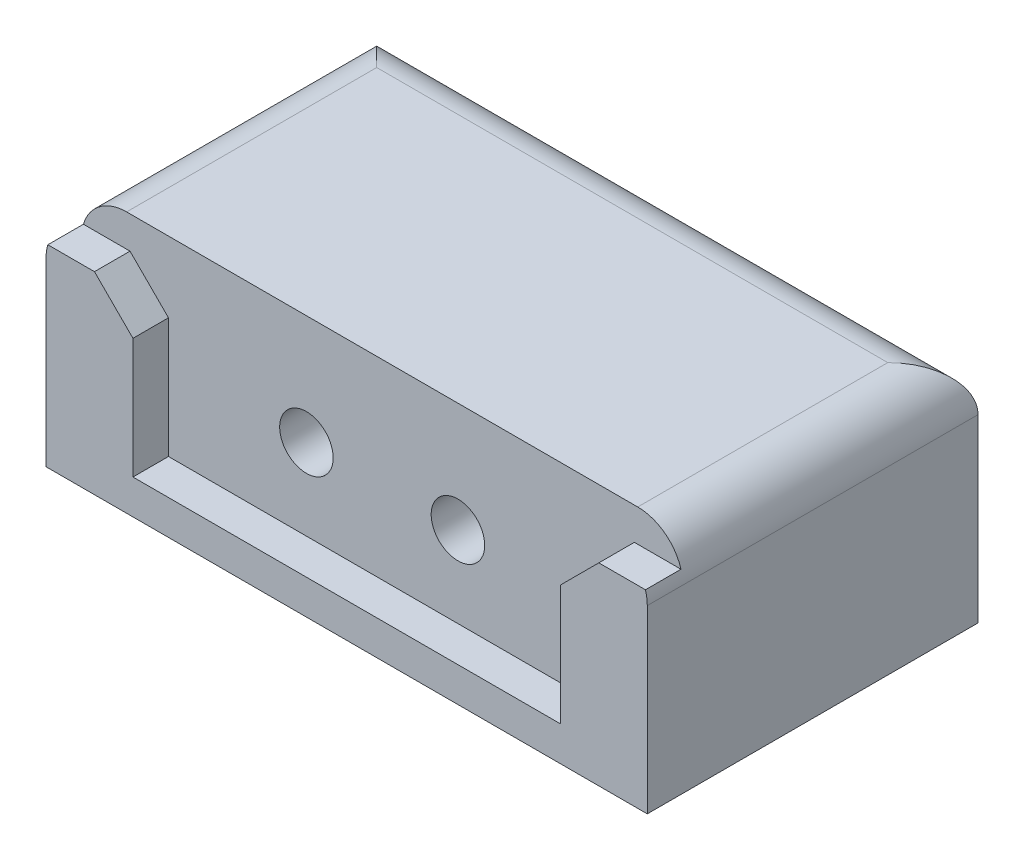
SolidWorks part; units mm, degrees
ref_plane "Front Plane" through (0, 0, 0) normal (0, 0, 1) x (1, 0, 0)
ref_plane "Top Plane" through (0, 0, 0) normal (0, 1, 0) x (1, 0, 0)
ref_plane "Right Plane" through (0, 0, 0) normal (1, 0, 0) x (0, 0, -1)
sketch "Sketch1" plane through (0, 0, 0) normal (0, 0, 1) x (1, 0, 0)
  line L1 (-12.7, 4.7625) -> (12.7, 4.7625)
  line L2 (-12.7, 4.7625) -> (-12.7, -4.7625)
  line L3 (-12.7, -4.7625) -> (12.7, -4.7625)
  line L4 (12.7, 4.7625) -> (12.7, -4.7625)
  line L5 (0, -4.7625) -> (0, 4.7625) construction
  line L6 (-12.7, 0) -> (12.7, 0) construction
  point P0 (0, 0)
  dimension "D1" = 25.4
  dimension "D2" = 9.525
extrude "Boss-Extrude1" add sketch "Sketch1" along normal blind 13.97
sketch "Sketch2" plane through (0, 0, 13.97) normal (0, 0, 1) x (1, 0, 0)
  line L5 (12.7, 3.525) -> (10.6, 3.525)
  line L6 (12.7, -4.7625) -> (12.7, 4.7625) construction
  line L7 (10.6, 3.525) -> (8.9, 1.825)
  line L8 (8.9, 1.825) -> (8.9, -3.175)
  line L9 (8.9, -3.175) -> (-8.9, -3.175)
  line L10 (-8.9, -3.175) -> (-8.9, 1.825)
  line L11 (-8.9, 1.825) -> (-10.6, 3.525)
  line L12 (-10.6, 3.525) -> (-12.6816, 3.525)
  line L13 (-12.6816, 3.525) -> (-12.7, 4.7625)
  line L14 (-12.7, 4.7625) -> (-12.7, -4.7625) construction
  line L15 (-12.7, 4.7625) -> (12.7, 4.7625)
  line L16 (12.7, 4.7625) -> (12.7, 3.525)
  line L17 (12.7, 4.7625) -> (-12.7, 4.7625) construction
  line L18 (-9.027, 1.7724) -> (-10.6526, 3.398)
  line L19 (-10.6526, 3.398) -> (-12.8067, 3.398)
  line L20 (-12.8067, 3.398) -> (-12.8289, 4.8895)
  line L21 (-12.8289, 4.8895) -> (12.827, 4.8895)
  line L22 (12.827, 4.8895) -> (12.827, 3.398)
  line L23 (12.827, 3.398) -> (10.6526, 3.398)
  line L24 (10.6526, 3.398) -> (9.027, 1.7724)
  line L25 (9.027, 1.7724) -> (9.027, -3.302)
  line L26 (9.027, -3.302) -> (-9.027, -3.302)
  line L27 (-9.027, -3.302) -> (-9.027, 1.7724)
  line M2 (12.7, -4.7625) -> (12.7, 4.7625)
  line M3 (12.7, 4.7625) -> (-12.7, 4.7625)
  line M4 (-12.7, 4.7625) -> (-12.7, -4.7625)
  dimension "D1" = 3.8
  dimension "D2" = 3.8
  dimension "D3" = 2.1
  dimension "D4" = 1.2375
  dimension "D5" = 25.3816
  dimension "D6" = 7.9375
  dimension "D7" = 0.127
extrude "Cut-Extrude1" cut sketch "Sketch2" against normal blind 1.5011 contours L13 L12 L11 L10 L9 L8 L7 L5 M2 M3 | L27 L26 L25 L24 L23 L5 L7 L8 L9 L10 L11 L12 L13 L19 L18 M2 M4
hole_wizard "#4-40 Tapped Hole1" positions "Sketch3" profile "Sketch4" tap size "#4-40" standard "ANSI Inch" end condition through all
sketch "Sketch3" plane through (0, 0, 12.4689) normal (0, 0, 1) x (1, 0, 0)
  point P0 (-3.2, 0.125)
  point P2 (3.2, 0.125)
  point P5 (0, 0)
  point P6 (0, 0)
  point P7 (0, 0)
  dimension "D1" = 6.4
  dimension "D2" = 3.2
  dimension "D3" = 0.125
cosmetic thread "Hole Thread1" parameters "D2"=2.8448
cosmetic thread "Hole Thread2" parameters "D2"=2.8448
sketch "Sketch4" plane through (-3.2, 0.125, 12.4689) normal (1, 0, 0) x (0, -1, 0)
  line L0 (0, 0) -> (0, 12.4689)
  line L1 (0, 12.4689) -> (1.1303, 12.4689)
  line L2 (1.1303, 12.4689) -> (1.1303, 0)
  line L5 (1.1303, 0) -> (0, 0)
  line L11 (0, -6.35) -> (0, 107.95) construction
  dimension "Thru Tap Drill Dia." = 2.2606
  dimension "Thru Tap Drill Depth" = 12.4689
sketch "Sketch5" plane through (0, -4.7625, 0) normal (0, -1, 0) x (1, 0, 0)
  line L0 (0, 0) -> (0, 13.97) construction
  line L1 (-12.7, 13.97) -> (12.7, 13.97) construction
  line L3 (-12.7, 13.97) -> (-12.7, 0) construction
  line L4 (12.7, 13.97) -> (12.7, 0) construction
  circle A0 centre (-6.985, 6.985) radius 2.6543
  circle A1 centre (6.985, 6.985) radius 2.6543
  point P4 (0, 6.985)
  dimension "D1" = 5.3086
  dimension "D2" = 5.715
  dimension "D3" = 5.715
extrude "Cut-Extrude2" cut sketch "Sketch5" against normal blind 7.62
fillet "Fillet1" radius 1.905 3 edges at (-12.7, 4.7625, 6.2344) (0, 4.7625, 0) (12.7, 4.7625, 6.2344)
